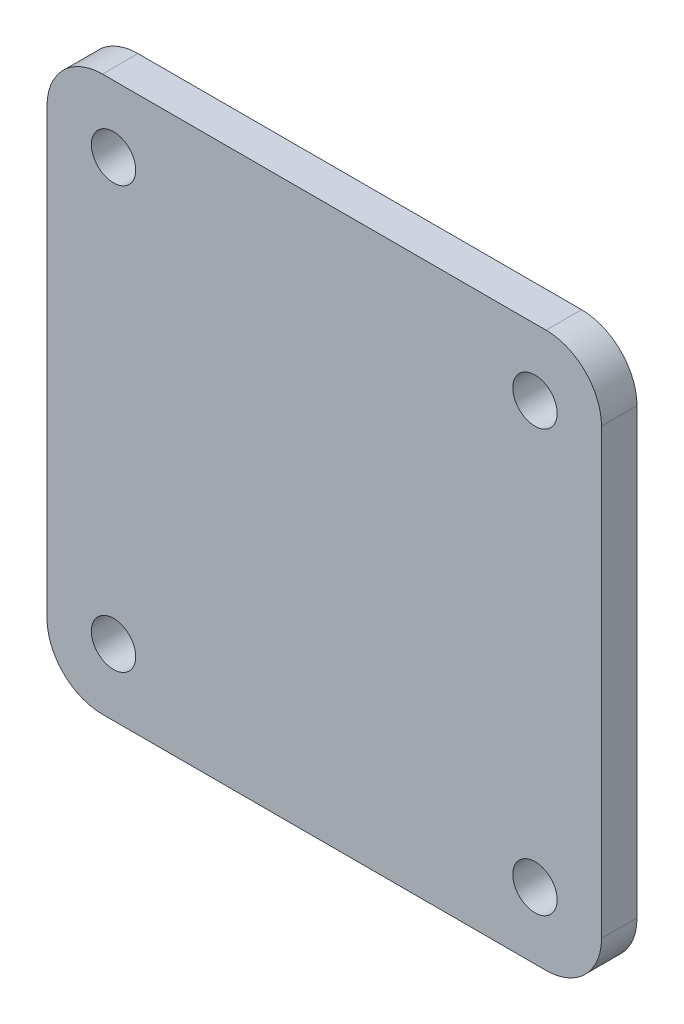
SolidWorks part; units mm, degrees
ref_plane "前视基准面" through (0, 0, 0) normal (0, 0, 1) x (1, 0, 0)
ref_plane "上视基准面" through (0, 0, 0) normal (0, 1, 0) x (1, 0, 0)
ref_plane "右视基准面" through (0, 0, 0) normal (1, 0, 0) x (0, 0, -1)
sketch "草图1" plane through (0, 0, 0) normal (0, 0, 1) x (1, 0, 0)
  line L1 (-12.5, 12.5) -> (12.5, 12.5)
  line L2 (-12.5, 12.5) -> (-12.5, -12.5)
  line L3 (-12.5, -12.5) -> (12.5, -12.5)
  line L4 (12.5, 12.5) -> (12.5, -12.5)
  line L5 (0, -12.5) -> (0, 12.5) construction
  line L6 (-12.5, 0) -> (12.5, 0) construction
  circle A0 centre (-9.5, 9.5) radius 1
  circle A1 centre (9.5, 9.5) radius 1
  circle A2 centre (9.5, -9.5) radius 1
  circle A3 centre (-9.5, -9.5) radius 1
  point P0 (0, 0)
  point P11 (-11.1637, 7.7116)
  point P12 (-9.1036, 10.0501)
  dimension "D3" = 3
  dimension "D5" = 2
  dimension "D1" = 25
  dimension "D2" = 25
  dimension "D4" = 3
extrude "凸台-拉伸1" add sketch "草图1" along normal blind 1.6
fillet "圆角1" radius 2.5 4 edges at (-12.5, 12.5, 0.8) (-12.5, -12.5, 0.8) (12.5, -12.5, 0.8) (12.5, 12.5, 0.8)
